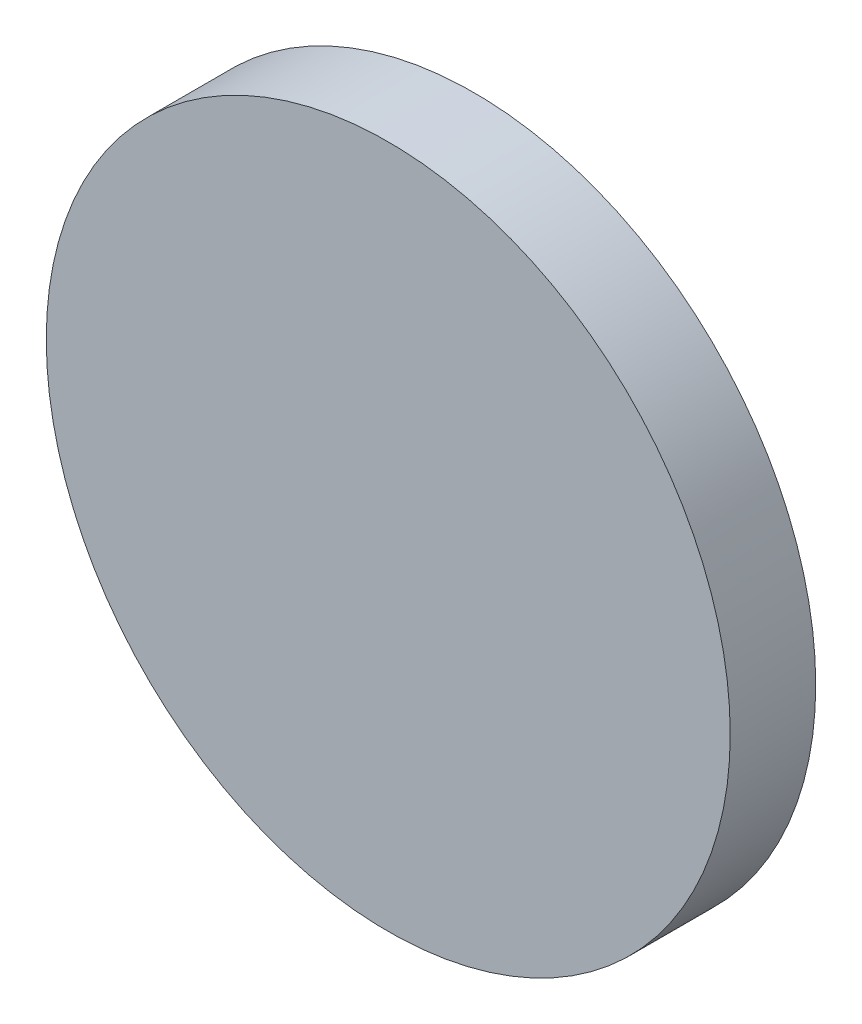
SolidWorks part; units mm, degrees
material "Nickel"
ref_plane "Front Plane" through (0, 0, 0) normal (0, 0, 1) x (1, 0, 0)
ref_plane "Top Plane" through (0, 0, 0) normal (0, 1, 0) x (1, 0, 0)
ref_plane "Right Plane" through (0, 0, 0) normal (1, 0, 0) x (0, 0, -1)
sketch "Sketch1" plane through (0, 0, 0) normal (0, 0, 1) x (1, 0, 0)
  circle A0 centre (0, 0) radius 20
  dimension "D1" = 40
extrude "Boss-Extrude1" add sketch "Sketch1" along normal blind 5
